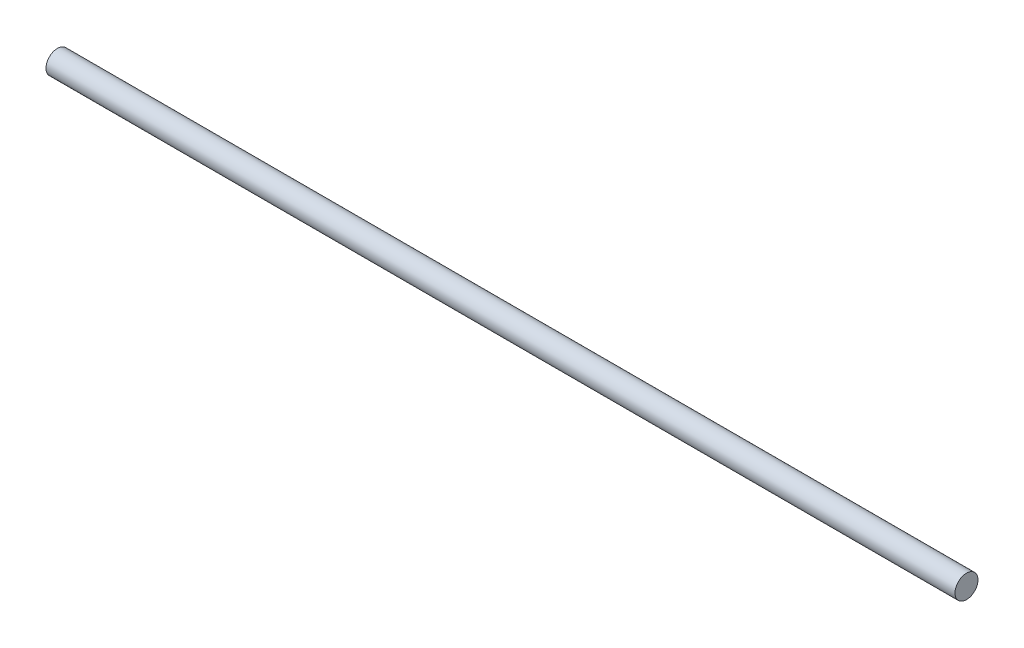
SolidWorks part; units mm, degrees
material "Stainless Steel (ferritic)"
ref_plane "Front Plane" through (0, 0, 0) normal (0, 0, 1) x (1, 0, 0)
ref_plane "Top Plane" through (0, 0, 0) normal (0, 1, 0) x (1, 0, 0)
ref_plane "Right Plane" through (0, 0, 0) normal (1, 0, 0) x (0, 0, -1)
sketch "Sketch1" plane through (0, 0, 0) normal (1, 0, 0) x (0, 0, -1)
  circle A0 centre (0, 0) radius 6.35
  dimension "D1" = 12.7
extrude "Boss-Extrude1" add sketch "Sketch1" along normal blind 501.65
